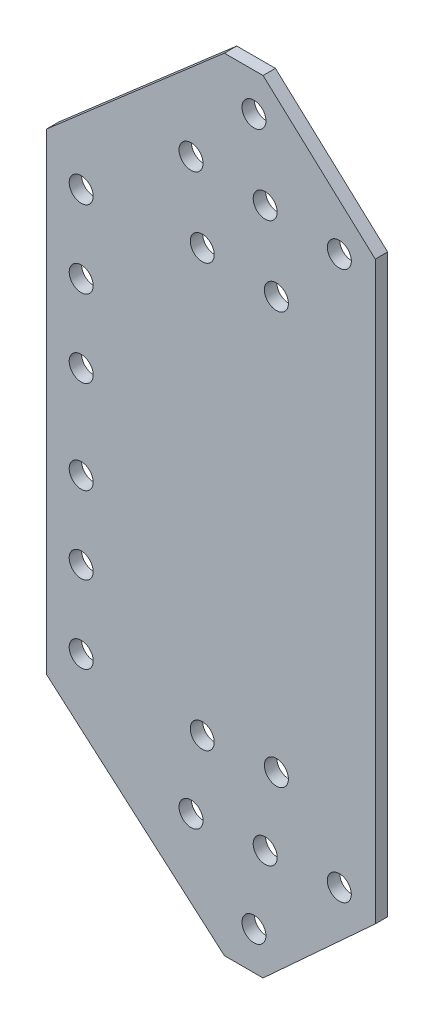
SolidWorks part; units mm, degrees
ref_plane "前视基准面" through (0, 0, 0) normal (0, 0, 1) x (1, 0, 0)
ref_plane "上视基准面" through (0, 0, 0) normal (0, 1, 0) x (1, 0, 0)
ref_plane "右视基准面" through (0, 0, 0) normal (1, 0, 0) x (0, 0, -1)
sketch "草图1" plane through (0, 0, 0) normal (0, 0, 1) x (1, 0, 0)
  line L0 (-1048.2762, 8.5678) -> (48951.7238, 8.5678) construction
  line L1 (29.462, -941.1536) -> (29.462, 49058.8464) construction
  line L2 (-395.538, 313.5678) -> (-395.538, -296.4322)
  line L3 (-395.538, -296.4322) -> (-165.538, -496.4322)
  line L4 (-165.538, -496.4322) -> (-115.538, -496.4322)
  line L5 (-115.538, -496.4322) -> (29.462, -363.4322)
  line L6 (29.462, -363.4322) -> (29.462, 380.5678)
  line L7 (-115.538, 513.5678) -> (29.462, 380.5678)
  line L8 (-165.538, 513.5678) -> (-115.538, 513.5678)
  line L9 (-395.538, 313.5678) -> (-165.538, 513.5678)
  point P19 (29.462, 8.5678)
  point P22 (-395.538, 8.5678)
  dimension "D1" = 305
  dimension "D2" = 230
  dimension "D3" = 50
  dimension "D5" = 133
  dimension "D6" = 200
extrude "拉伸1" add sketch "草图1" along normal blind 16
sketch "草图2" plane through (0, 0, 16) normal (0, 0, 1) x (1, 0, 0)
  line L0 (-1395.538, 8.5678) -> (48604.462, 8.5678) construction
  line L1 (-395.538, 313.5678) -> (-395.538, -296.4322) construction
  line L2 (-445.538, 442.5678) -> (-445.538, -425.4322) construction
  line L3 (-183.038, -1329.6426) -> (-183.038, 48670.3574) construction
  line L4 (-445.538, -715.9787) -> (-445.538, 49284.0213) construction
  line L5 (-445.538, 442.5678) -> (-445.538, -425.4322) construction
  line L6 (-445.538, -425.4322) -> (-45.538, -425.4322) construction
  line L7 (-165.538, -496.4322) -> (-115.538, -496.4322) construction
  line L8 (-445.538, 442.5678) -> (-445.538, -425.4322) construction
  line L9 (-194.105, -264.2369) -> (-112.7789, -352.4757) construction
  line L10 (-445.538, 8.5678) -> (-194.105, -264.2369) construction
  line L11 (-445.538, 8.5678) -> (-194.105, -264.2369) construction
  line L12 (-194.105, -264.2369) -> (-445.538, 8.5678) construction
  line L13 (-194.105, -264.2369) -> (-153.442, -308.3563) construction
  line L14 (-167.9282, -403.3045) -> (-57.6297, -301.6469) construction
  line L15 (-208.5912, 376.3208) -> (-98.2927, 274.6632) construction
  line L16 (-208.5912, -359.1851) -> (-98.2927, -257.5276) construction
  line L17 (-167.9282, 420.4401) -> (-57.6297, 318.7826) construction
  line L18 (-194.105, 281.3726) -> (-153.442, 325.492) construction
  line L19 (-194.105, 281.3726) -> (-445.538, 8.5678) construction
  line L20 (-445.538, 8.5678) -> (-194.105, 281.3726) construction
  line L21 (-445.538, 8.5678) -> (-194.105, 281.3726) construction
  line L22 (-194.105, 281.3726) -> (-112.7789, 369.6114) construction
  line L23 (-445.538, 442.5678) -> (-45.538, 442.5678) construction
  line L24 (-445.538, 733.1144) -> (-445.538, -49266.8856) construction
  line L25 (-183.038, 1346.7783) -> (-183.038, -48653.2217) construction
  circle A0 centre (-350.538, -51.4322) radius 15.5
  circle A1 centre (-350.538, -251.4322) radius 15.5
  circle A2 centre (-350.538, -151.4322) radius 15.5
  circle A3 centre (-194.105, -264.2369) radius 15.5
  circle A4 centre (-112.7789, -352.4757) radius 15.5
  circle A5 centre (-98.2927, -257.5276) radius 15.5
  circle A6 centre (-208.5912, -359.1851) radius 15.5
  circle A7 centre (-127.2651, -447.4238) radius 15.5
  circle A8 centre (-16.9667, -345.7663) radius 15.5
  circle A9 centre (-16.9667, 362.902) radius 15.5
  circle A10 centre (-127.2651, 464.5595) radius 15.5
  circle A11 centre (-208.5912, 376.3208) radius 15.5
  circle A12 centre (-98.2927, 274.6632) radius 15.5
  circle A13 centre (-112.7789, 369.6114) radius 15.5
  circle A14 centre (-194.105, 281.3726) radius 15.5
  circle A15 centre (-350.538, 168.5678) radius 15.5
  circle A16 centre (-350.538, 268.5678) radius 15.5
  circle A17 centre (-350.538, 68.5678) radius 15.5
  point P5 (-395.538, 8.5678)
  dimension "D3" = 31
  dimension "D6" = 31
  dimension "D8" = 31
  dimension "D13" = 31
  dimension "D16" = 31
  dimension "D18" = 31
  dimension "D1" = 212.5
  dimension "D2" = 50
  dimension "D4" = 60
  dimension "D5" = 45
  dimension "D7" = 200
  dimension "D9" = 100
  dimension "D10" = 590.2169
  dimension "D11" = 434
  dimension "D12" = 371
  dimension "D14" = 232.1952
  dimension "D15" = 120
  dimension "D17" = 75
  dimension "D19" = 75
extrude "拉伸2" cut sketch "草图2" against normal through all
